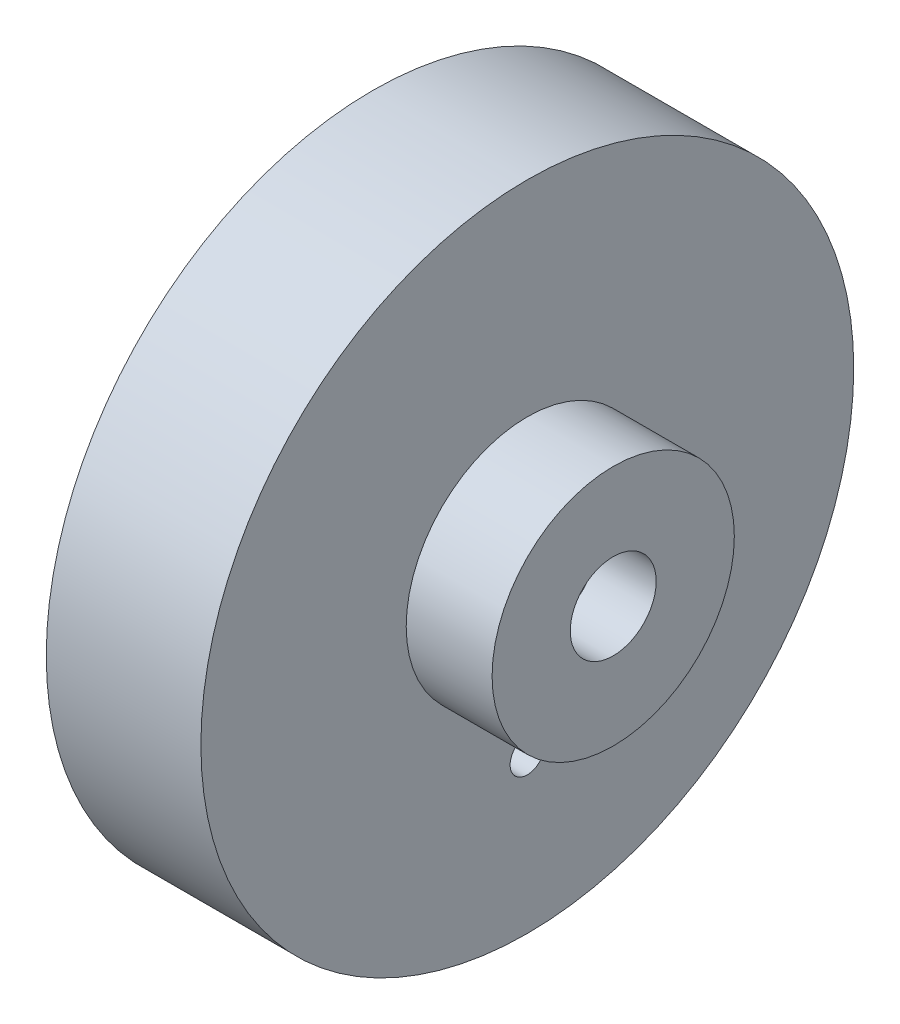
SolidWorks part; units mm, degrees
ref_plane "Plane1" through (0, 0, 0) normal (0, 0, 1) x (1, 0, 0)
ref_plane "Plane2" through (0, 0, 0) normal (0, 1, 0) x (1, 0, 0)
ref_plane "Plane3" through (0, 0, 0) normal (1, 0, 0) x (0, 0, -1)
sketch "HoldingSke" plane through (0, 0, 0) normal (0, 1, 0) x (1, 0, 0)
  line L0 (0, 0) -> (0.8387, -0.5446)
  line L1 (-15, 0) -> (100, 0) construction
  line L2 (0, 0) -> (-2.1039, 2.3779)
  line L3 (0, 0) -> (-11.863, 4.5341)
  line L4 (0, 0) -> (7.2428, 4.7035)
  line L5 (0, 0) -> (-23.7986, -8.8762)
  line L6 (0, 0) -> (-10.5278, -7.1032)
  line L7 (-2.1039, 2.3779) -> (3.3635, 27.1825)
  line L8 (-76.2, 3.3779) -> (-54.61, 3.3779)
  line L9 (-71.009, 38.7566) -> (-53.1078, 45.2721)
  line L10 (-76.2, 71.12) -> (104.1128, 71.12)
  line L11 (0, 0) -> (-5, 0)
  line L12 (-76.2, 101.6) -> (-76.162, 101.6)
  line L13 (24.9733, 27.94) -> (52.9518, 28.4284)
  line L14 (24.9733, 27.94) -> (24.9743, 27.94)
  line L15 (24.9733, 27.94) -> (100.4006, 29.5858)
  circle A0 centre (0, 0) radius 19
  circle A1 centre (0, 0) radius 12.7
  circle A2 centre (0, 0) radius 12.7
  dimension "MHD" = 25.4
  dimension "Hub_dia" = 25.4
  dimension "Diameter" = 38
  dimension "Num_teeth" = 33
  dimension "Pitch" = 1
  dimension "Overall_len" = 25.4
  dimension "Show_teeth" = 33
  dimension "Thickness" = 12.7
  dimension "OAL" = 25.4001
  dimension "T_dim" = 21.59
  dimension "Ap" = 20
  dimension "H" = 19.05
  dimension "Pitch_radius" = 180.3128
  dimension "Width" = 5
  dimension "Backlash" = 0.038
  dimension "Addendum_fac" = 1
  dimension "Dedendum_fac" = 1.25
  dimension "Clearance_fac" = 0.25
  dimension "Dedendum_add" = 0.001
  dimension "Module" = 1
sketch "BasProSke" plane through (0, 0, 0) normal (0, 1, 0) x (1, 0, 0)
  line L0 (-10, 0) -> (60, 0) construction
  line L1 (0, 15.5) -> (0, 19)
  line L2 (0, 15.5) -> (5, 15.5)
  line L3 (5, 15.5) -> (5, 19)
  line L4 (5, 19) -> (0, 19)
  dimension "Diameter" = 38
  dimension "Thickness" = 5
  dimension "Inside_diameter" = 31
revolve "Base-Revolve" add sketch "BasProSke" angle 360 about L0
sketch "TooCutSke" plane through (0, 0, 0) normal (1, 0, 0) x (0, 0, -1)
  line L3 (0.8801, 16.4765) -> (0.8801, 53.6633) construction
  line L4 (0, 0) -> (0, 59.563) construction
  line L5 (0, 0) -> (-6.4949, 68.0181) construction
  line L6 (-6.7635, 13.3721) -> (36.345, 17.4884) construction
  circle A0 centre (0, 0) radius 16.5 construction
  circle A1 centre (0, 0) radius 17.751 construction
  circle A2 centre (0, 0) radius 13.9544 construction
  circle A3 centre (0, 0) radius 15.4746 construction
  arc A4 (1.2267, 15.4259) -> (0.2294, 17.7495) centre (-6.7635, 13.3721) ccw
  arc A5 (1.2267, 15.4259) -> (-1.2267, 15.4259) centre (0, 0) ccw
  arc A6 (0.2294, 17.7495) -> (-0.2294, 17.7495) centre (0, 0) ccw
  arc A7 (-0.2294, 17.7495) -> (-1.2267, 15.4259) centre (6.7635, 13.3721) ccw
  dimension "Pitch_dia" = 33
  dimension "Base_dia" = 27.9089
  dimension "Root_dia" = 35.502
  dimension "Overcut_dia" = 30.9492
  dimension "Flank_rad" = 8.25
  dimension "Half_ang" = 5.455
  dimension "Half_CT" = 0.8801
extrude "ToothCut" cut sketch "TooCutSke" along normal through all
fillet "Breaks" [suppressed] radius 0.1
fillet "RootFillets" [suppressed] radius 0.251
pattern_circular "TeethCuts" count 33 every 10.909 about axis through (-10, 0, 0) along (1, 0, 0) of "RootFillets", "Breaks", "ToothCut"
sketch "Esquisse1" plane through (5, 0, 0) normal (1, 0, 0) x (0, 0, -1)
  circle A0 centre (0, 0) radius 19
  circle A2 centre (0, 0) radius 17.751
extrude "Boss.-Extru.1" add sketch "Esquisse1" along normal blind 1
sketch "Esquisse2" plane through (6, 0, 0) normal (1, 0, 0) x (0, 0, -1)
  circle A0 centre (0, 0) radius 19
  circle A1 centre (0, 0) radius 5.05
  dimension "D1" = 10.1
extrude "Boss.-Extru.2" add sketch "Esquisse2" along normal blind 3
sketch "Esquisse3" plane through (6, 0, 0) normal (-1, 0, 0) x (0, 0, 1)
  circle A0 centre (0, -10) radius 1
  circle A1 centre (0, 0) radius 5.05 construction
  dimension "D1" = 2
  dimension "D2" = 10
extrude "Enlèv. mat.-Extru.1" cut sketch "Esquisse3" against normal through all
sketch "Esquisse4" plane through (6, 0, 0) normal (-1, 0, 0) x (0, 0, 1)
  circle A0 centre (0, -10) radius 2
  dimension "D1" = 4
extrude "Enlèv. mat.-Extru.2" cut sketch "Esquisse4" against normal blind 1.5
sketch "Esquisse5" plane through (9, 0, 0) normal (1, 0, 0) x (0, 0, -1)
  circle A0 centre (0, 0) radius 5.05
  circle A1 centre (0, 0) radius 7.05
  circle A2 centre (0, 0) radius 5.05 construction
  dimension "D1" = 2
extrude "Boss.-Extru.3" add sketch "Esquisse5" along normal blind 5
sketch "Esquisse6" plane through (14, 0, 0) normal (1, 0, 0) x (0, 0, -1)
  circle A0 centre (0, 0) radius 7
  circle A1 centre (0, 0) radius 2.5
  dimension "D1" = 5
extrude "Boss.-Extru.4" add sketch "Esquisse6" against normal blind 3.5
chamfer "Chanfrein1" distance 0.5 angle 45 1 edges at (6, 0, -5.05)
equation "' \"Module@HoldingSke\" = 6.35"
equation "' \"Num_teeth@HoldingSke\" = 24"
equation "' \"Ap@HoldingSke\" =  14.5"
equation "' \"Ap@HoldingSke\" = 14.5"
equation "' \"Width@HoldingSke\" = 12"
equation "' \"Diameter@HoldingSke\" = 8 * 25.4"
equation "' \"Show_teeth@HoldingSke\" = 100"
equation "' \"Backlash@HoldingSke\" = 0.009 * 25.4"
equation "' \"Addendum_fac@HoldingSke\" = 1.0"
equation "' \"Dedendum_fac@HoldingSke\" = 1.25"
equation "' \"Dedendum_add@HoldingSke\" = 0.00005 * 25.4"
equation "' \"Clearance_fac@HoldingSke\" = 0.25"
equation "\"Pitch@HoldingSke\" = 1 / \"Module@HoldingSke\" "
equation "\"Overcut_dia@TooCutSke\" = (\"Num_teeth@HoldingSke\" - 2 * \"Addendum_fac@HoldingSke\") / \"Pitch@HoldingSke\" - 0.002 * 25.4"
equation "\"Pitch_dia@TooCutSke\" = \"Num_teeth@HoldingSke\" / \"Pitch@HoldingSke\""
equation "\"Base_dia@TooCutSke\" = \"Num_teeth@HoldingSke\" / \"Pitch@HoldingSke\" * cos((\"Ap@HoldingSke\"  * 3.14159265 / 180)) * 0.90"
equation "\"Root_dia@TooCutSke\" = \"Num_teeth@HoldingSke\"  / \"Pitch@HoldingSke\" + 2 *  \"Dedendum_fac@HoldingSke\"/ \"Pitch@HoldingSke\" + \"Dedendum_add@HoldingSke\" * 2"
equation "\"Half_ang@TooCutSke\" = 180 / \"Num_teeth@HoldingSke\""
equation "\"Half_CT@TooCutSke\" = \"Num_teeth@HoldingSke\" / \"Pitch@HoldingSke\" * sin((3.14159265 / 2 / \"Num_teeth@HoldingSke\")) / 2 + 10 * \"Backlash@HoldingSke\" / 4"
equation "\"Flank_rad@TooCutSke\" = \"Num_teeth@HoldingSke\" / \"Pitch@HoldingSke\" / 4"
equation "\"Radius@RootFillets\"= \"Clearance_fac@HoldingSke\" / \"Pitch@HoldingSke\" + \"Dedendum_add@HoldingSke\""
equation "\"Break_rad@Breaks\" = 0.02 / \"Pitch@HoldingSke\" * 5"
equation "\"Num_teeth@TeethCuts\" = int( \"Show_teeth@HoldingSke\" ) + 1"
equation "\"Num_teeth@TeethCuts\" = ((sgn( \"Num_teeth@TeethCuts\" - \"Num_teeth@HoldingSke\" )-1)*( \"Num_teeth@TeethCuts\" - \"Num_teeth@HoldingSke\" ))/-2+ \"Num_teeth@HoldingSke\""
equation "\"Num_teeth@TeethCuts\" = ((sgn( \"Num_teeth@TeethCuts\" - 2.0)+1)*( \"Num_teeth@TeethCuts\" - 2.0))/2 +2.0"
equation "\"Angle@TeethCuts\" = 360.0 / \"Num_teeth@HoldingSke\""
equation "\"Diameter@BasProSke\" = \"Num_teeth@HoldingSke\"  / \"Pitch@HoldingSke\" + 2 *  \"Dedendum_fac@HoldingSke\"/ \"Pitch@HoldingSke\" + \"Dedendum_add@HoldingSke\" * 2 + 0.002 * 25.4"
equation "\"Diameter@BasProSke\" = ((sgn( \"Diameter@BasProSke\"  - \"Diameter@HoldingSke\" )+1)*( \"Diameter@BasProSke\"  - \"Diameter@HoldingSke\" ))/2 + \"Diameter@HoldingSke\""
equation "\"Inside_diameter@BasProSke\" =  (\"Num_teeth@HoldingSke\" - 2 * \"Addendum_fac@HoldingSke\") / \"Pitch@HoldingSke\" "
equation "\"Thickness@BasProSke\"  = \"Width@HoldingSke\""
